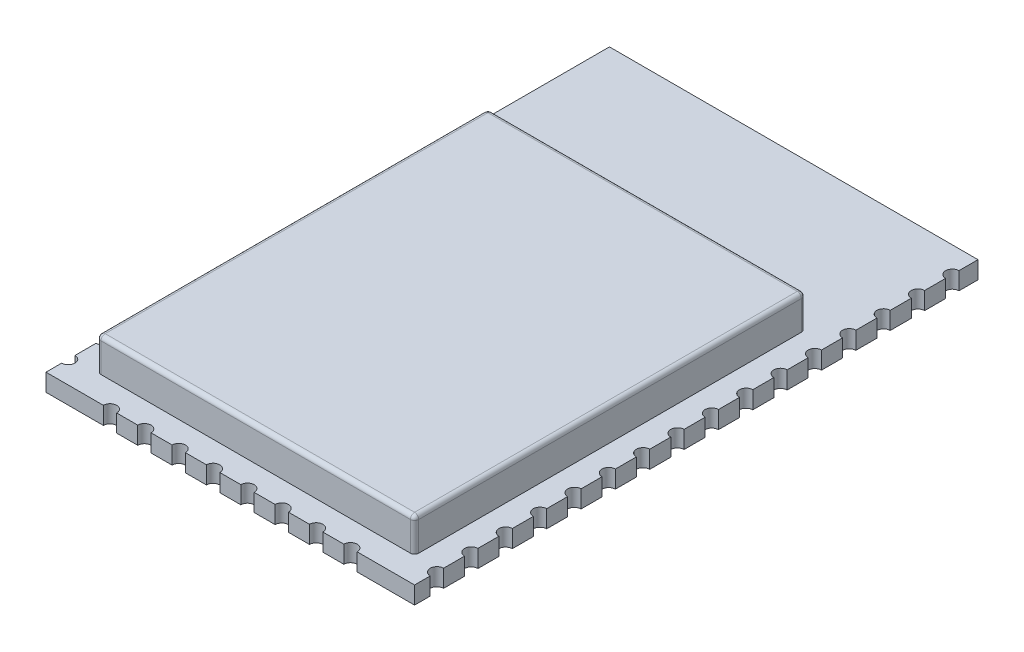
SolidWorks part; units mm, degrees
ref_plane "Plan de face" through (0, 0, 0) normal (0, 0, 1) x (1, 0, 0)
ref_plane "Plan de dessus" through (0, 0, 0) normal (0, 1, 0) x (1, 0, 0)
ref_plane "Plan de droite" through (0, 0, 0) normal (1, 0, 0) x (0, 0, -1)
sketch "Esquisse1" plane through (0, 0, 0) normal (0, 1, 0) x (1, 0, 0)
  line L1 (0, 0) -> (22.098, 0)
  line L2 (0, 0) -> (0, 33.782)
  line L3 (0, 33.782) -> (22.098, 33.782)
  line L4 (22.098, 0) -> (22.098, 33.782)
  dimension "D1" = 22.098
  dimension "D2" = 33.782
extrude "Boss.-Extru.1" add sketch "Esquisse1" along normal blind 1.048
sketch "Esquisse2" plane through (0, 1.048, 0) normal (0, 1, 0) x (1, 0, 0)
  line L0 (0, 33.782) -> (0, 0) construction
  line L1 (1.524, 1.524) -> (20.574, 1.524)
  line L2 (1.524, 1.524) -> (1.524, 24.967)
  line L3 (1.524, 24.967) -> (20.574, 24.967)
  line L4 (20.574, 1.524) -> (20.574, 24.967)
  line L5 (22.098, 0) -> (22.098, 33.782) construction
  line L6 (0, 0) -> (22.098, 0) construction
  dimension "D1" = 1.524
  dimension "D2" = 1.524
  dimension "D3" = 1.524
extrude "Boss.-Extru.2" add sketch "Esquisse2" along normal blind 2
sketch "Esquisse3" plane through (0, 1.048, 0) normal (0, 1, 0) x (1, 0, 0)
  line L0 (0, 33.782) -> (0, 0) construction
  line L1 (22.098, 33.782) -> (0, 33.782) construction
  line L2 (0, 26.4604) -> (0, 25.6604)
  line L3 (0, 26.0604) -> (22.098, 26.0604) construction
  line L4 (22.098, 0) -> (22.098, 33.782) construction
  line L5 (22.098, 26.4604) -> (22.098, 25.6604)
  line L6 (22.098, 24.4004) -> (22.098, 23.6004)
  line L7 (0, 24.4004) -> (0, 23.6004)
  line L8 (22.098, 22.3404) -> (22.098, 21.5404)
  line L9 (0, 22.3404) -> (0, 21.5404)
  line L10 (22.098, 20.2804) -> (22.098, 19.4804)
  line L11 (0, 20.2804) -> (0, 19.4804)
  line L12 (22.098, 18.2204) -> (22.098, 17.4204)
  line L13 (0, 18.2204) -> (0, 17.4204)
  line L14 (22.098, 16.1604) -> (22.098, 15.3604)
  line L15 (0, 16.1604) -> (0, 15.3604)
  line L16 (22.098, 14.1004) -> (22.098, 13.3004)
  line L17 (0, 14.1004) -> (0, 13.3004)
  line L18 (22.098, 12.0404) -> (22.098, 11.2404)
  line L19 (0, 12.0404) -> (0, 11.2404)
  line L20 (22.098, 9.9804) -> (22.098, 9.1804)
  line L21 (0, 9.9804) -> (0, 9.1804)
  line L22 (22.098, 7.9204) -> (22.098, 7.1204)
  line L23 (0, 7.9204) -> (0, 7.1204)
  line L24 (22.098, 5.8604) -> (22.098, 5.0604)
  line L25 (0, 5.8604) -> (0, 5.0604)
  line L26 (22.098, 3.8004) -> (22.098, 3.0004)
  line L27 (0, 3.8004) -> (0, 3.0004)
  line L28 (22.098, 1.7404) -> (22.098, 0.9404)
  line L29 (0, 1.7404) -> (0, 0.9404)
  line L30 (22.098, 26.4604) -> (22.098, 24.4004) construction
  line L31 (22.098, 28.5204) -> (22.098, 27.7204)
  line L32 (22.098, 30.5804) -> (22.098, 29.7804)
  line L33 (22.098, 32.6404) -> (22.098, 31.8404)
  line L34 (22.098, 26.4604) -> (22.098, 28.5204) construction
  line L35 (0, 0) -> (22.098, 0) construction
  line L36 (11.049, 0) -> (11.049, 2.3181) construction
  line L37 (10.419, 0) -> (9.619, 0)
  line L38 (12.479, 0) -> (11.679, 0)
  line L39 (14.539, 0) -> (13.739, 0)
  line L40 (16.599, 0) -> (15.799, 0)
  line L41 (18.659, 0) -> (17.859, 0)
  line L42 (9.619, 0) -> (11.679, 0) construction
  line L43 (8.359, 0) -> (7.559, 0)
  line L44 (6.299, 0) -> (5.499, 0)
  line L45 (4.239, 0) -> (3.439, 0)
  line L46 (9.619, 0) -> (7.559, 0) construction
  arc A0 (0, 25.6604) -> (0, 26.4604) centre (0, 26.0604) ccw
  arc A1 (22.098, 26.4604) -> (22.098, 25.6604) centre (22.098, 26.0604) ccw
  arc A2 (22.098, 24.4004) -> (22.098, 23.6004) centre (22.098, 24.0004) ccw
  arc A3 (0, 23.6004) -> (0, 24.4004) centre (0, 24.0004) ccw
  arc A4 (22.098, 22.3404) -> (22.098, 21.5404) centre (22.098, 21.9404) ccw
  arc A5 (0, 21.5404) -> (0, 22.3404) centre (0, 21.9404) ccw
  arc A6 (22.098, 20.2804) -> (22.098, 19.4804) centre (22.098, 19.8804) ccw
  arc A7 (0, 19.4804) -> (0, 20.2804) centre (0, 19.8804) ccw
  arc A8 (22.098, 18.2204) -> (22.098, 17.4204) centre (22.098, 17.8204) ccw
  arc A9 (0, 17.4204) -> (0, 18.2204) centre (0, 17.8204) ccw
  arc A10 (22.098, 16.1604) -> (22.098, 15.3604) centre (22.098, 15.7604) ccw
  arc A11 (0, 15.3604) -> (0, 16.1604) centre (0, 15.7604) ccw
  arc A12 (22.098, 14.1004) -> (22.098, 13.3004) centre (22.098, 13.7004) ccw
  arc A13 (0, 13.3004) -> (0, 14.1004) centre (0, 13.7004) ccw
  arc A14 (22.098, 12.0404) -> (22.098, 11.2404) centre (22.098, 11.6404) ccw
  arc A15 (0, 11.2404) -> (0, 12.0404) centre (0, 11.6404) ccw
  arc A16 (22.098, 9.9804) -> (22.098, 9.1804) centre (22.098, 9.5804) ccw
  arc A17 (0, 9.1804) -> (0, 9.9804) centre (0, 9.5804) ccw
  arc A18 (22.098, 7.9204) -> (22.098, 7.1204) centre (22.098, 7.5204) ccw
  arc A19 (0, 7.1204) -> (0, 7.9204) centre (0, 7.5204) ccw
  arc A20 (22.098, 5.8604) -> (22.098, 5.0604) centre (22.098, 5.4604) ccw
  arc A21 (0, 5.0604) -> (0, 5.8604) centre (0, 5.4604) ccw
  arc A22 (22.098, 3.8004) -> (22.098, 3.0004) centre (22.098, 3.4004) ccw
  arc A23 (0, 3.0004) -> (0, 3.8004) centre (0, 3.4004) ccw
  arc A24 (22.098, 1.7404) -> (22.098, 0.9404) centre (22.098, 1.3404) ccw
  arc A25 (0, 0.9404) -> (0, 1.7404) centre (0, 1.3404) ccw
  arc A26 (22.098, 28.5204) -> (22.098, 27.7204) centre (22.098, 28.1204) ccw
  arc A27 (22.098, 30.5804) -> (22.098, 29.7804) centre (22.098, 30.1804) ccw
  arc A28 (22.098, 32.6404) -> (22.098, 31.8404) centre (22.098, 32.2404) ccw
  arc A29 (9.619, 0) -> (10.419, 0) centre (10.019, 0) cw
  arc A30 (11.679, 0) -> (12.479, 0) centre (12.079, 0) cw
  arc A31 (13.739, 0) -> (14.539, 0) centre (14.139, 0) cw
  arc A32 (15.799, 0) -> (16.599, 0) centre (16.199, 0) cw
  arc A33 (17.859, 0) -> (18.659, 0) centre (18.259, 0) cw
  arc A34 (7.559, 0) -> (8.359, 0) centre (7.959, 0) cw
  arc A35 (5.499, 0) -> (6.299, 0) centre (5.899, 0) cw
  arc A36 (3.439, 0) -> (4.239, 0) centre (3.839, 0) cw
  dimension "D2" = 0.4
  dimension "D3" = 0.4
  dimension "D7" = 0.4
  dimension "D1" = 7.7216
  dimension "D4" = 2.06
  dimension "D6" = 2.06
  dimension "D8" = 1.03
  dimension "D9" = 2.06
  dimension "D11" = 2.06
  dimension "D5" = 13
  dimension "D10" = 5
extrude "Enlèv. mat.-Extru.1" cut sketch "Esquisse3" against normal blind 2
fillet "Congé1" radius 0.25 8 edges at (1.524, 2.048, -24.967) (11.049, 3.048, -24.967) (20.574, 2.048, -24.967) (20.574, 3.048, -13.2455) (20.574, 2.048, -1.524) (11.049, 3.048, -1.524) (1.524, 3.048, -13.2455) (1.524, 2.048, -1.524)
